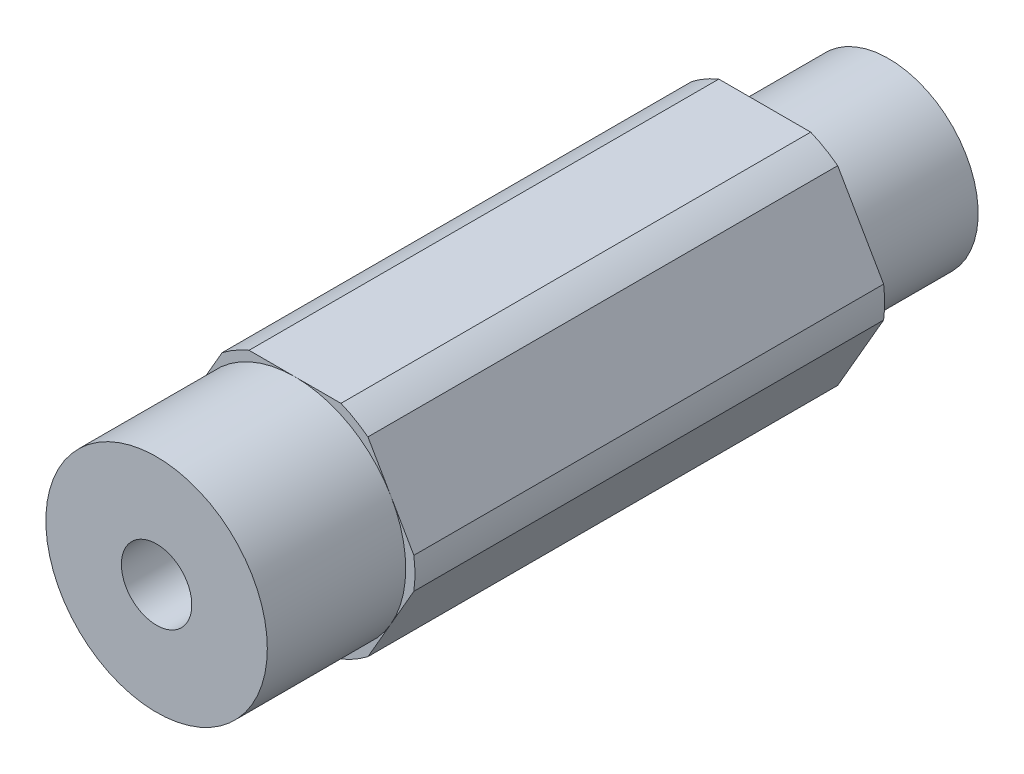
SolidWorks part; units mm, degrees
material "7075-T6 (SN)"
ref_plane "Front Plane" through (0, 0, 0) normal (0, 0, 1) x (1, 0, 0)
ref_plane "Top Plane" through (0, 0, 0) normal (0, 1, 0) x (1, 0, 0)
ref_plane "Right Plane" through (0, 0, 0) normal (1, 0, 0) x (0, 0, -1)
sketch "Sketch1" plane through (0, 0, 0) normal (0, 0, 1) x (1, 0, 0)
  line L1 (7.3323, 0) -> (3.6662, 6.35)
  line L2 (3.6662, 6.35) -> (-3.6662, 6.35)
  line L3 (-3.6662, 6.35) -> (-7.3323, 0)
  line L4 (-7.3323, 0) -> (-3.6662, -6.35)
  line L5 (-3.6662, -6.35) -> (3.6662, -6.35)
  line L6 (3.6662, -6.35) -> (7.3323, 0)
  circle A0 centre (0, 0) radius 6.35 construction
  circle A1 centre (0, 0) radius 2.0193
  circle A2 centre (0, 0) radius 6.875
  dimension "D1" = 12.7
  dimension "D2" = 4.0386
  dimension "D3" = 13.75
extrude "Boss-Extrude1" add sketch "Sketch1" along normal mid plane 41.9862 contours L1 A2 L2 L3 L4 L5 L6 A1
hole_wizard "#10-32 Tapped Hole1" positions "3DSketch1" profile "Sketch3" tap size "#10-32" standard "ANSI Inch"
sketch3d "3DSketch1"
  circle A0 centre (0, 0, -20.9931) radius 2.0193 construction
  circle A1 centre (0, 0, 20.9931) radius 2.0193 construction
  point P0 (0, 0, 20.9931)
  point P2 (0, 0, -20.9931)
  point P6 (0, 0, -18.9738)
  point P9 (0, 0, 23.0124)
sketch "Sketch3" plane through (0, 0, 20.9931) normal (1, 0, 0) x (0, -1, 0)
  line L0 (0, 0) -> (0, 13.1513)
  line L1 (0, 13.1513) -> (2.0193, 11.938)
  line L2 (2.0193, 11.938) -> (2.0193, 0)
  line L5 (2.0193, 0) -> (0, 0)
  line L10 (0, 13.1513) -> (-2.0193, 11.938) construction
  line L11 (0, -6.35) -> (0, 107.95) construction
  dimension "Tap Drill Dia." = 4.0386
  dimension "Tap Drill Depth" = 11.938
  dimension "Drill Angle" = 118
cosmetic thread "Hole Thread1" parameters "D1"=9.652, "D2"=4.826
cosmetic thread "Hole Thread2" parameters "D1"=9.652, "D2"=4.826
sketch "Sketch4" plane through (0, 0, 20.9931) normal (0, 0, 1) x (1, 0, 0)
  circle A0 centre (0, 0) radius 6.35
  dimension "D1" = 12.7
extrude "Cut-Extrude-Thin1" cut sketch "Sketch4" against normal blind 7.9375 thin
sketch "Sketch5" plane through (0, 0, -20.9931) normal (0, 0, -1) x (-1, 0, 0)
  circle A0 centre (0, 0) radius 5.125
  dimension "D1" = 10.25
extrude "Cut-Extrude-Thin2" cut sketch "Sketch5" against normal blind 7.112 thin
equation "\"D3@Sketch1\"=13.75mm"
equation "\"D1@Sketch5\"=10.25mm"
